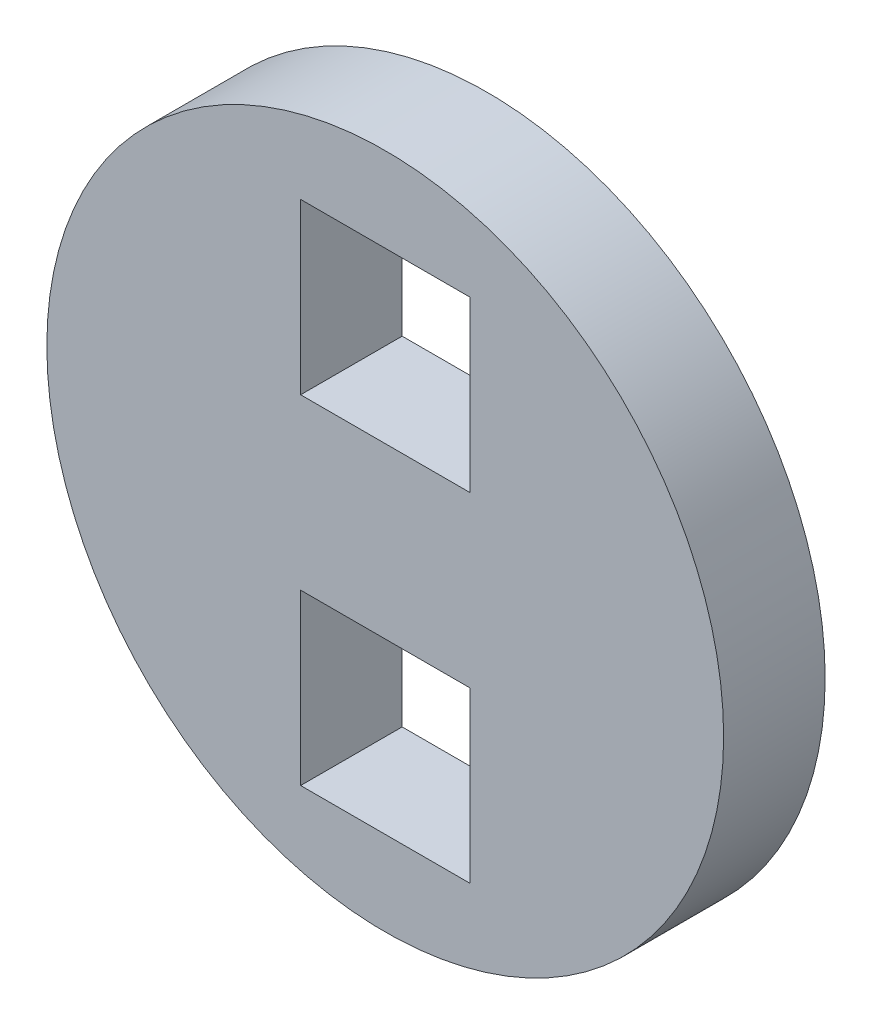
SolidWorks part; units mm, degrees
ref_plane "Plan de face" through (0, 0, 0) normal (0, 0, 1) x (1, 0, 0)
ref_plane "Plan de dessus" through (0, 0, 0) normal (0, 1, 0) x (1, 0, 0)
ref_plane "Plan de droite" through (0, 0, 0) normal (1, 0, 0) x (0, 0, -1)
sketch "Esquisse1" plane through (0, 0, 0) normal (0, 0, 1) x (1, 0, 0)
  circle A2 centre (0, 0) radius 10
  line B0 (-2.5, -2.5) -> (-2.5, -7.5)
  line B1 (-2.5, -2.5) -> (2.5, -2.5)
  line B2 (2.5, -2.5) -> (2.5, -7.5)
  line B3 (-2.5, -7.5) -> (2.5, -7.5)
  line B4 (-2.5, 2.5) -> (-2.5, 7.5)
  line B5 (-2.5, 2.5) -> (2.5, 2.5)
  line B6 (2.5, 2.5) -> (2.5, 7.5)
  line B7 (-2.5, 7.5) -> (2.5, 7.5)
  line B8 (0, 0) -> (-6.301, 0) construction
  circle B9 centre (0, 0) radius 1.5 construction
sketch_block_instance "Trou M3 plots 5mm-52"
sketch_block "Trou M3 plots 5mm" parameters "D2"=3, "D5"=3, "D1"=5, "D3"=5, "D4"=8
extrude "Boss.-Extru.1" add sketch "Esquisse1" along normal blind 3
